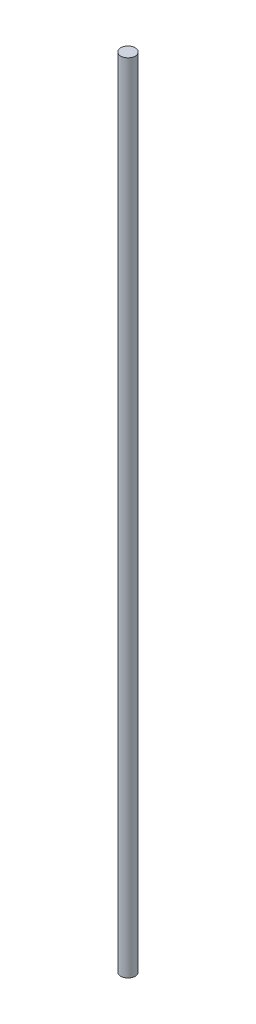
SolidWorks part; units mm, degrees
ref_plane "Front Plane" through (0, 0, 0) normal (0, 0, 1) x (1, 0, 0)
ref_plane "Top Plane" through (0, 0, 0) normal (0, 1, 0) x (1, 0, 0)
ref_plane "Right Plane" through (0, 0, 0) normal (1, 0, 0) x (0, 0, -1)
sketch "Sketch1" plane through (0, 0, 0) normal (0, 1, 0) x (1, 0, 0)
  circle A0 centre (0, 0) radius 5
  dimension "D1" = 10
extrude "Boss-Extrude1" add sketch "Sketch1" along normal blind 550
